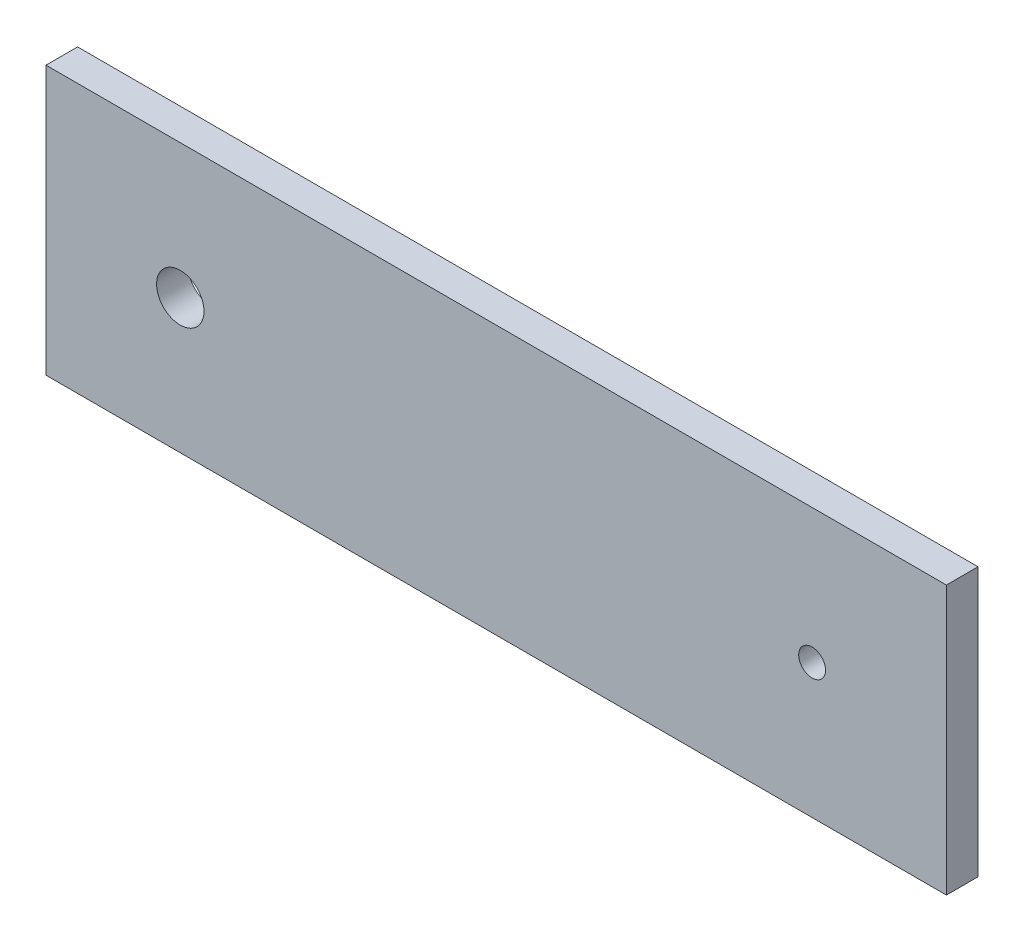
SolidWorks part; units mm, degrees
ref_plane "前视基准面" through (0, 0, 0) normal (0, 0, 1) x (1, 0, 0)
ref_plane "上视基准面" through (0, 0, 0) normal (0, 1, 0) x (1, 0, 0)
ref_plane "右视基准面" through (0, 0, 0) normal (1, 0, 0) x (0, 0, -1)
other "Configuration Table"
sketch "草图1" plane through (0, 0, 0) normal (0, 0, 1) x (1, 0, 0)
  line L1 (-17, -17) -> (97, -17)
  line L2 (-17, -17) -> (-17, 17)
  line L3 (-17, 17) -> (97, 17)
  line L4 (97, -17) -> (97, 17)
  line L5 (-17, -17) -> (97, 17) construction
  line L6 (-17, 17) -> (97, -17) construction
  circle A0 centre (0, 0) radius 3
  circle A1 centre (80, 0) radius 1.7
  point P0 (40, 0)
extrude "凸台-拉伸1" add sketch "草图1" along normal mid plane 4
